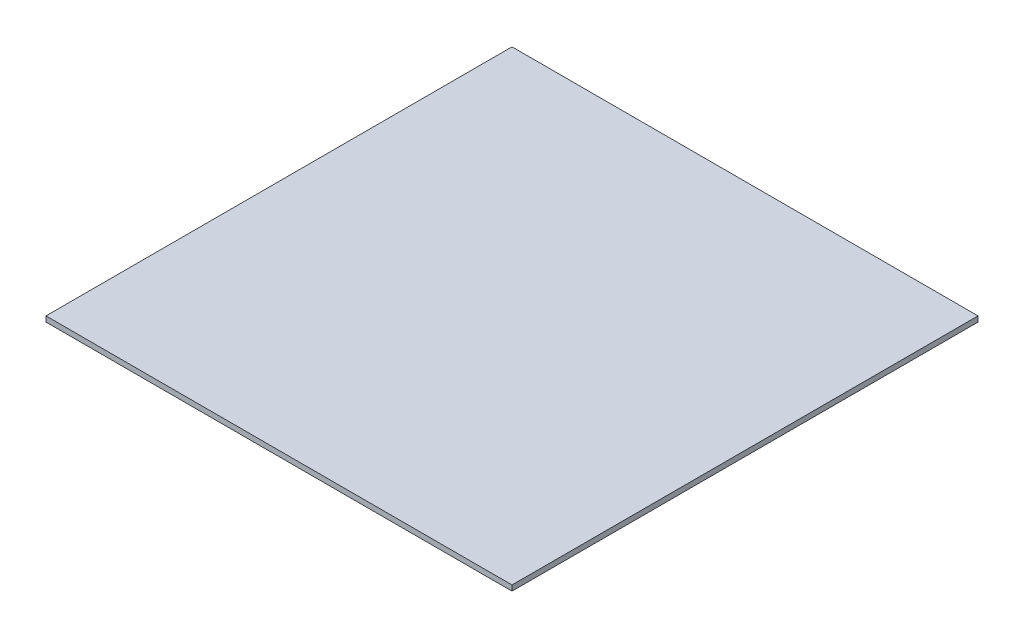
SolidWorks part; units mm, degrees
material "PVC 0.007 Plasticized"
ref_plane "Front Plane" through (0, 0, 0) normal (0, 0, 1) x (1, 0, 0)
ref_plane "Top Plane" through (0, 0, 0) normal (0, 1, 0) x (1, 0, 0)
ref_plane "Right Plane" through (0, 0, 0) normal (1, 0, 0) x (0, 0, -1)
sketch "Sketch2" plane through (0, 0, 0) normal (0, 1, 0) x (1, 0, 0)
  line L1 (-5002.8387, 2278.4516) -> (-4570.8387, 2278.4516)
  line L2 (-5002.8387, 2278.4516) -> (-5002.8387, 1846.4516)
  line L3 (-5002.8387, 1846.4516) -> (-4570.8387, 1846.4516)
  line L4 (-4570.8387, 2278.4516) -> (-4570.8387, 1846.4516)
  dimension "D1" = 432
  dimension "D2" = 432
extrude "Boss-Extrude1" add sketch "Sketch2" along normal blind 5
